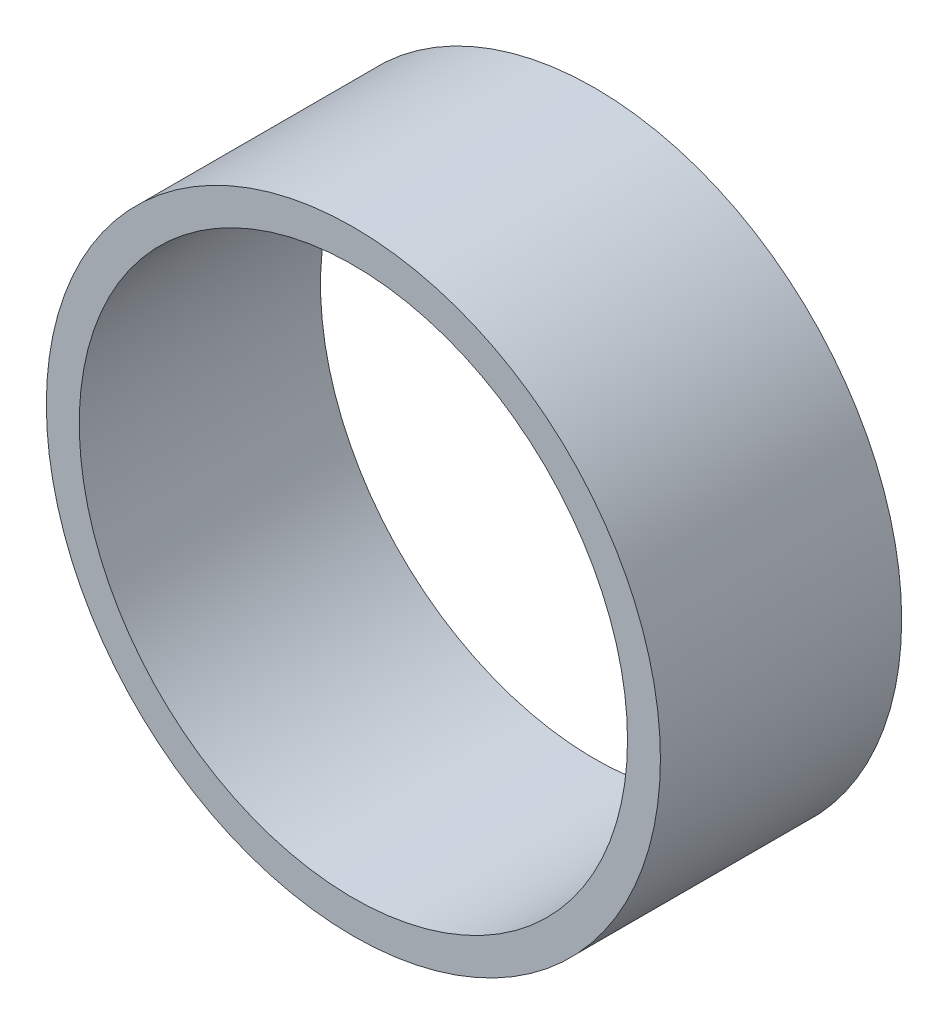
SolidWorks part; units mm, degrees
material "1.0050 (E295)"
ref_plane "Front Plane" through (0, 0, 0) normal (0, 0, 1) x (1, 0, 0)
ref_plane "Top Plane" through (0, 0, 0) normal (0, 1, 0) x (1, 0, 0)
ref_plane "Right Plane" through (0, 0, 0) normal (1, 0, 0) x (0, 0, -1)
sketch "Sketch1" plane through (0, 0, 0) normal (0, 0, 1) x (1, 0, 0)
  circle A0 centre (0, 0) radius 25
  circle A1 centre (0, 0) radius 28
  dimension "D1" = 50
  dimension "D2" = 56
extrude "Boss-Extrude1" add sketch "Sketch1" along normal blind 22
